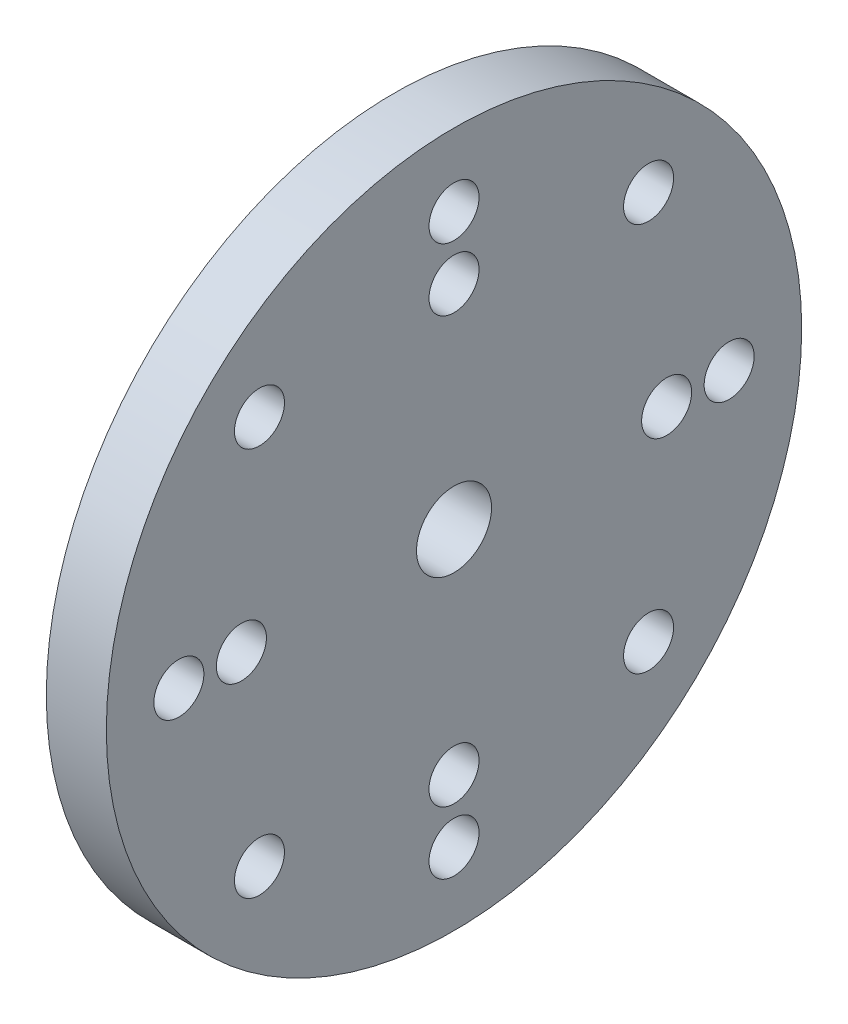
SolidWorks part; units mm, degrees
ref_plane "Front Plane" through (0, 0, 0) normal (0, 0, 1) x (1, 0, 0)
ref_plane "Top Plane" through (0, 0, 0) normal (0, 1, 0) x (1, 0, 0)
ref_plane "Right Plane" through (0, 0, 0) normal (1, 0, 0) x (0, 0, -1)
sketch "Sketch1" plane through (0, 0, 0) normal (0, 0, 1) x (1, 0, 0)
  line L0 (0, 0) -> (20.558, 0) construction
  line L1 (0, 0) -> (0, 4.95)
  line L2 (0, 4.95) -> (2, 4.95)
  line L3 (2, 4.95) -> (2, 13.9)
  line L4 (2, 13.9) -> (4.4, 13.9)
  line L5 (4.4, 13.9) -> (4.4, 0)
  line L6 (4.4, 0) -> (0, 0)
  dimension "D1" = 2
  dimension "D2" = 2.4
  dimension "D3" = 27.8
  dimension "D4" = 9.9
revolve "Revolve1" add sketch "Sketch1" angle 360 about L0
sketch "Sketch2" plane through (4.4, 0, 0) normal (1, 0, 0) x (0, 0, -1)
  circle A0 centre (0, 11) radius 1
  circle A2 centre (0, 0) radius 11 construction
  dimension "D1" = 2
  dimension "D2" = 22
extrude "Cut-Extrude1" cut sketch "Sketch2" against normal blind 10
sketch "Sketch3" plane through (4.4, 0, 0) normal (1, 0, 0) x (0, 0, -1)
  circle A0 centre (0, 8.5) radius 1
  circle A1 centre (0, 0) radius 8.5 construction
  circle A2 centre (0, 11) radius 1 construction
  dimension "D1" = 17
extrude "Cut-Extrude2" cut sketch "Sketch3" against normal blind 10
pattern_circular "CirPattern1" count 8 over 360 about axis through (0, 0, 0) along (1, 0, 0) of "Cut-Extrude1"
pattern_circular "CirPattern2" count 4 over 360 about axis through (0, 0, 0) along (1, 0, 0) of "Cut-Extrude2"
sketch "Sketch5" plane through (4.4, 0, 0) normal (1, 0, 0) x (0, 0, -1)
  circle A0 centre (0, 0) radius 1.5
  dimension "D1" = 3
extrude "Cut-Extrude3" cut sketch "Sketch5" against normal blind 10
